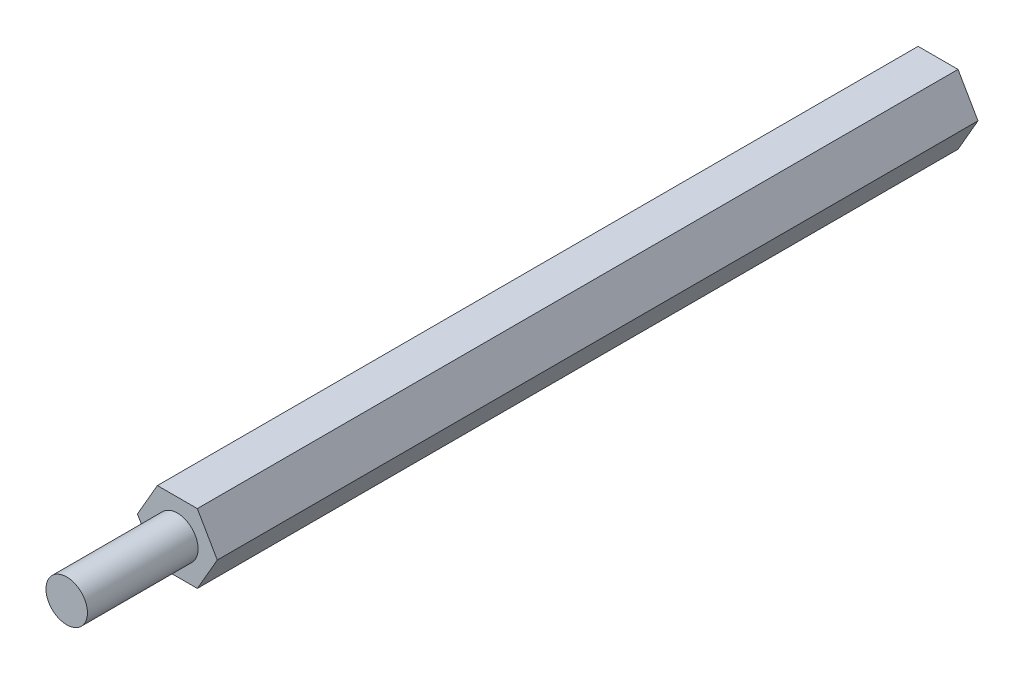
SolidWorks part; units mm, degrees
ref_plane "前视基准面" through (0, 0, 0) normal (0, 0, 1) x (1, 0, 0)
ref_plane "上视基准面" through (0, 0, 0) normal (0, 1, 0) x (1, 0, 0)
ref_plane "右视基准面" through (0, 0, 0) normal (1, 0, 0) x (0, 0, -1)
sketch "草图1" plane through (0, 0, 0) normal (0, 0, 1) x (1, 0, 0)
  line L0 (-28.6627, 0) -> (33.6774, 0) construction
  line L1 (1.4434, -2.5) -> (2.8868, 0)
  line L2 (2.8868, 0) -> (1.4434, 2.5)
  line L3 (1.4434, 2.5) -> (-1.4434, 2.5)
  line L4 (-1.4434, 2.5) -> (-2.8868, 0)
  line L5 (-2.8868, 0) -> (-1.4434, -2.5)
  line L6 (-1.4434, -2.5) -> (1.4434, -2.5)
  circle A0 centre (0, 0) radius 2.5 construction
  dimension "D1" = 5
extrude "拉伸1" add sketch "草图1" along normal blind 55
sketch "草图2" plane through (0, 0, 55) normal (0, 0, 1) x (1, 0, 0)
  circle A0 centre (0, 0) radius 1.5
  dimension "D1" = 3
extrude "拉伸2" add sketch "草图2" along normal blind 8
hole_wizard "M3x0.5 螺纹孔1" positions "3D草图2" profile "草图5" tap size "M3x0.5" standard "ISO"
sketch3d "3D草图2"
  point P0 (0, 0, 0)
  point P2 (0, 0, 0)
  point P3 (0, 0, 0)
  point P4 (0, 0, 0)
sketch "草图5" plane through (0, 0, 0) normal (1, 0, 0) x (0, 1, 0)
  line L0 (0, 0) -> (0, 11.7511)
  line L1 (0, 11.7511) -> (1.25, 11)
  line L2 (1.25, 11) -> (1.25, 0)
  line L5 (1.25, 0) -> (0, 0)
  line L10 (0, 11.7511) -> (-1.25, 11) construction
  line L11 (0, -6.35) -> (0, 107.95) construction
  dimension "蹟恇謂郰芛眻噤" = 2.5
  dimension "蹟恇謂郰芛旮僅" = 11
  dimension "絳芛褒僅" = 118
cosmetic thread "孔螺蚊线1" parameters "D1"=6, "D2"=3
